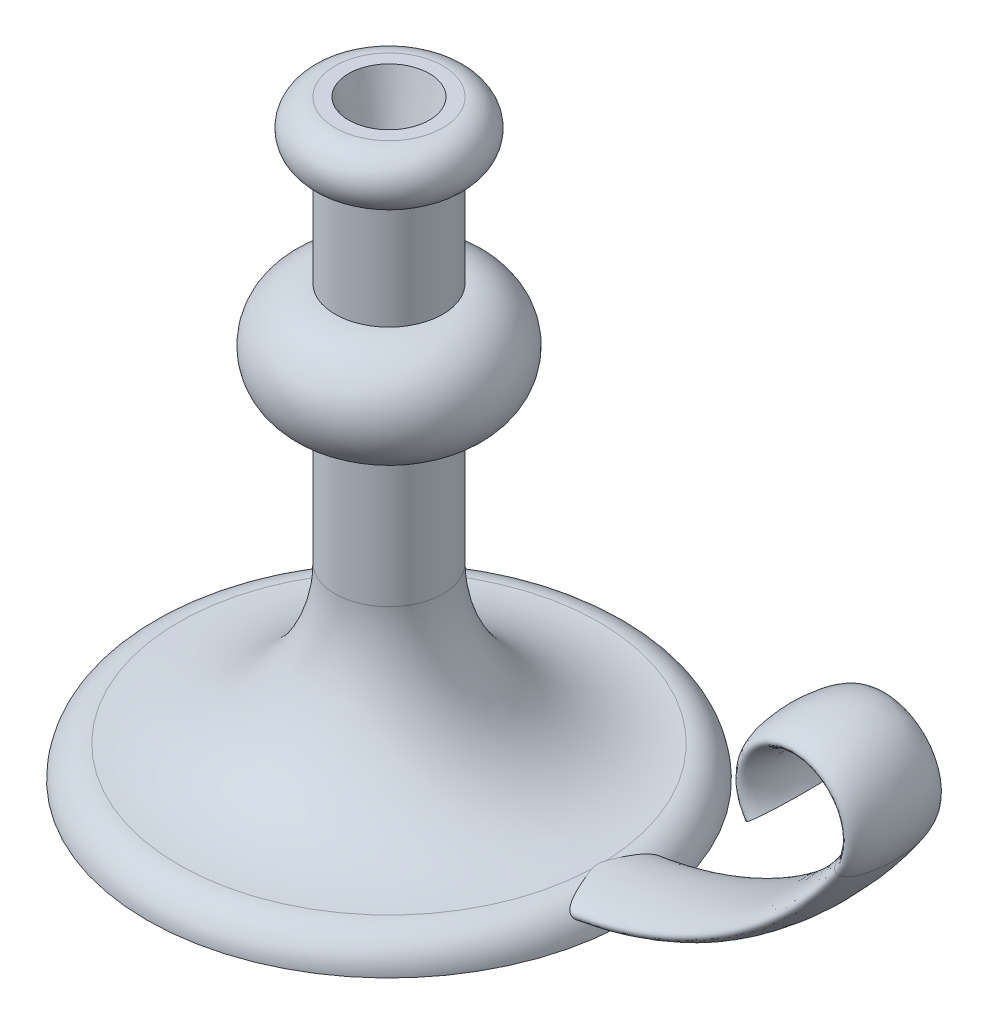
SolidWorks part; units mm, degrees
ref_plane "Front Plane" through (0, 0, 0) normal (0, 0, 1) x (1, 0, 0)
ref_plane "Top Plane" through (0, 0, 0) normal (0, 1, 0) x (1, 0, 0)
ref_plane "Right Plane" through (0, 0, 0) normal (1, 0, 0) x (0, 0, -1)
sketch "Sketch1" plane through (0, 0, 0) normal (0, 0, 1) x (1, 0, 0)
  line L0 (0, 0) -> (0, 220)
  line L1 (0, 220) -> (20, 220)
  line L2 (0, 0) -> (90, 0)
  line L3 (20, 200) -> (20, 160)
  line L4 (20, 120) -> (20, 70)
  arc A0 (20, 220) -> (20, 200) centre (20, 210) cw
  arc A1 (20, 160) -> (20, 120) centre (20, 140) cw
  arc A2 (20, 70) -> (78.1325, 11.8675) centre (78.1325, 70) ccw
  arc A3 (78.1325, 11.8675) -> (90, 0) centre (78.1325, 0) cw
  dimension "D4" = 10
  dimension "D5" = 20
  dimension "D9" = 20
  dimension "D10" = 78.1325
  dimension "D11" = 78.1325
  dimension "D1" = 220
  dimension "D2" = 20
  dimension "D3" = 90
  dimension "D6" = 40
  dimension "D7" = 150
  dimension "D8" = 20
revolve "Revolve1" add sketch "Sketch1" angle 360 about L0
sketch "Sketch2" plane through (0, 0, 0) normal (0, 0, 1) x (1, 0, 0)
  line L1 (0, 5.7997) -> (60, 5.7997)
  line L2 (0, 227.4356) -> (0, 175.1288) construction
  line L3 (0, 164) -> (0, 92) construction
  arc A0 (60, 5.7997) -> (183.5921, 70.7997) centre (60, 155.7997) ccw
  arc A1 (183.5921, 70.7997) -> (150.6342, 70.7997) centre (167.1131, 82.133) ccw
  arc A2 (-78.1325, 11.8675) -> (-90, 0) centre (-78.1325, 0) ccw construction
  dimension "D2" = 150
  dimension "D4" = 20
  dimension "D1" = 60
  dimension "D3" = 65
  dimension "D5" = 5.7997
sketch "Sketch3" plane through (0, 0, 0) normal (1, 0, 0) x (0, 0, -1)
  ellipse E0 centre (0, 5.7997) end of major axis (17.5, 5.7997) minor radius 5
  dimension "D1" = 35
  dimension "D2" = 10
sweep "Sweep1" add profiles "Sketch3" path "Sketch2"
sketch "Sketch4" plane through (0, 220, 0) normal (0, 1, 0) x (1, 0, 0)
  circle A0 centre (0, 0) radius 15
  dimension "D1" = 30
extrude "Cut-Extrude1" cut sketch "Sketch4" against normal blind 25 draft 15
